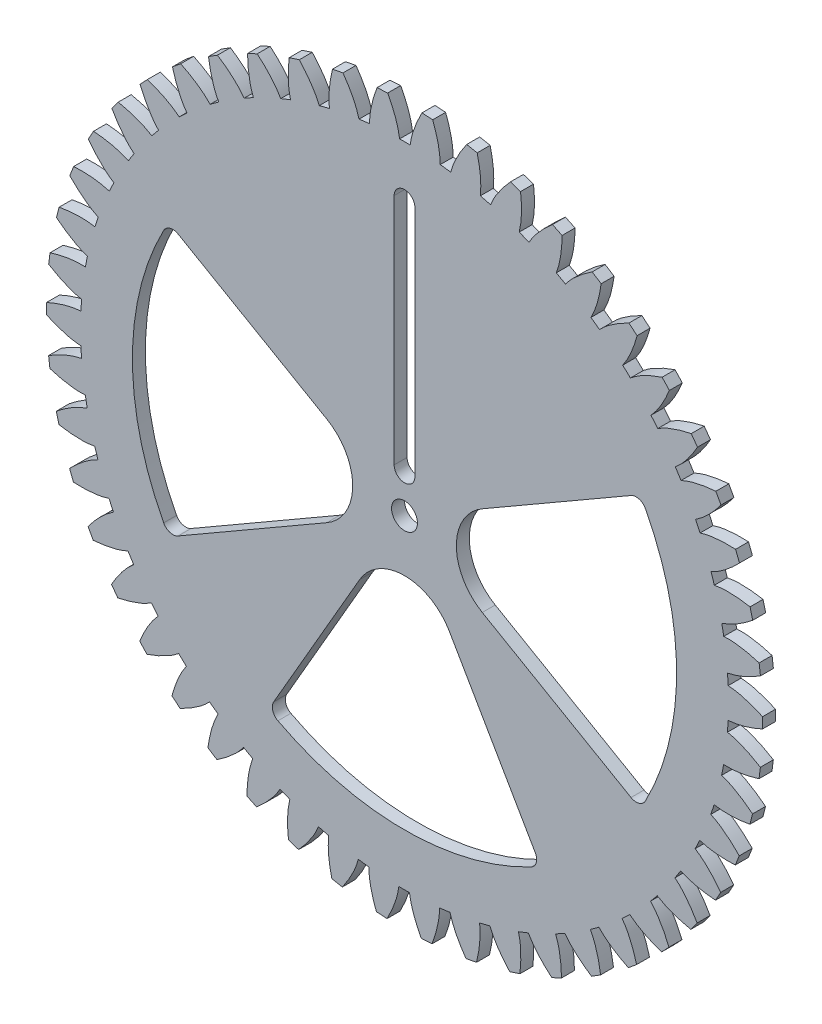
SolidWorks part; units mm, degrees
ref_plane "Front Plane" through (0, 0, 0) normal (0, 0, 1) x (1, 0, 0)
ref_plane "Top Plane" through (0, 0, 0) normal (0, 1, 0) x (1, 0, 0)
ref_plane "Right Plane" through (0, 0, 0) normal (1, 0, 0) x (0, 0, -1)
sketch "spiralSketch" plane through (0, 0, 0) normal (0, 0, 1) x (1, 0, 0)
  line L0 (30.4685, 172.8151) -> (35.6087, 171.8296)
  line L1 (8.5687, 175.2711) -> (13.7919, 174.9376)
  line L2 (51.8877, 167.6337) -> (56.8638, 166.0117)
  line L3 (72.4886, 159.8086) -> (77.2222, 157.5757)
  line L4 (91.9463, 149.4632) -> (96.3628, 146.6547)
  line L5 (109.954, 136.7607) -> (113.9836, 133.4208)
  line L6 (126.2277, 121.9014) -> (129.8069, 118.0828)
  line L7 (140.5106, 105.1197) -> (143.583, 100.8826)
  line L8 (152.5776, 86.6801) -> (155.0948, 82.0914)
  line L9 (162.2384, 66.8736) -> (164.1606, 62.0055)
  line L10 (169.3406, 46.0124) -> (170.6375, 40.9418)
  line L11 (173.7722, 24.4256) -> (174.4233, 19.2324)
  line L12 (175.4633, 2.4535) -> (175.4584, -2.7803)
  line L13 (174.3872, -19.5572) -> (173.7264, -24.7491)
  line L14 (170.5609, -41.2595) -> (169.2546, -46.3277)
  line L15 (164.0448, -62.3111) -> (162.1136, -67.1756)
  line L16 (154.9416, -82.38) -> (152.416, -86.9641)
  line L17 (143.3949, -101.1498) -> (140.3146, -105.3812)
  line L18 (129.5868, -118.3243) -> (126.0004, -122.1363)
  line L19 (113.735, -133.6328) -> (109.6992, -136.9652)
  line L20 (96.0895, -146.8339) -> (91.6679, -149.6342)
  line L21 (76.9287, -157.7193) -> (72.1909, -159.9433)
  line L22 (56.5546, -166.1173) -> (51.5754, -167.73)
  line L23 (35.2886, -171.8956) -> (30.1466, -172.8715)
  line L24 (13.4661, -174.963) -> (8.2423, -175.2868)
  line L25 (-8.5687, -175.2711) -> (-13.7919, -174.9376)
  line L26 (-30.4685, -172.8151) -> (-35.6087, -171.8296)
  line L27 (-51.8877, -167.6337) -> (-56.8638, -166.0117)
  line L28 (-72.4886, -159.8086) -> (-77.2222, -157.5757)
  line L29 (-91.9463, -149.4632) -> (-96.3628, -146.6547)
  line L30 (-109.954, -136.7607) -> (-113.9836, -133.4208)
  line L31 (-126.2277, -121.9014) -> (-129.8069, -118.0828)
  line L32 (-140.5106, -105.1197) -> (-143.583, -100.8826)
  line L33 (-152.5776, -86.6801) -> (-155.0948, -82.0914)
  line L34 (-162.2384, -66.8736) -> (-164.1606, -62.0055)
  line L35 (-169.3406, -46.0124) -> (-170.6375, -40.9418)
  line L36 (-173.7722, -24.4256) -> (-174.4233, -19.2324)
  line L37 (-175.4633, -2.4535) -> (-175.4584, 2.7803)
  line L38 (-174.3872, 19.5572) -> (-173.7264, 24.7491)
  line L39 (-170.5609, 41.2595) -> (-169.2546, 46.3277)
  line L40 (-164.0448, 62.3111) -> (-162.1136, 67.1756)
  line L41 (-154.9416, 82.38) -> (-152.416, 86.9641)
  line L42 (-143.3949, 101.1498) -> (-140.3146, 105.3812)
  line L43 (-129.5868, 118.3243) -> (-126.0004, 122.1363)
  line L44 (-113.735, 133.6328) -> (-109.6992, 136.9652)
  line L45 (-96.0895, 146.8339) -> (-91.6679, 149.6342)
  line L46 (-76.9287, 157.7193) -> (-72.1909, 159.9433)
  line L47 (-56.5546, 166.1173) -> (-51.5754, 167.73)
  line L48 (-35.2886, 171.8956) -> (-30.1466, 172.8715)
  line L49 (-13.4661, 174.963) -> (-8.2423, 175.2868)
  line L50 (0, 19.05) -> (0, 133.35) construction
  line L51 (-5.08, 19.05) -> (-5.08, 133.35)
  line L52 (5.08, 19.05) -> (5.08, 133.35)
  arc A2 (124.0747, 99.0305) -> (120.7741, 103.03) centre (0, 0) ccw
  arc A3 (135.5081, 82.6989) -> (132.7349, 87.0805) centre (0, 0) ccw
  arc A4 (144.8045, 65.0631) -> (142.6023, 69.7578) centre (0, 0) ccw
  arc A5 (151.8173, 46.4013) -> (150.2208, 51.3349) centre (0, 0) ccw
  arc A6 (156.4358, 27.0076) -> (155.4702, 32.1025) centre (0, 0) ccw
  arc A7 (158.5872, 7.1881) -> (158.2678, 12.3638) centre (0, 0) ccw
  arc A8 (155.3925, -32.4768) -> (156.3703, -27.3843) centre (0, 0) ccw
  arc A9 (158.2376, -12.7449) -> (158.5694, -7.5699) centre (0, 0) ccw
  arc A10 (150.0967, -51.6965) -> (151.7051, -46.7667) centre (0, 0) ccw
  arc A11 (142.4339, -70.101) -> (144.6474, -65.4117) centre (0, 0) ccw
  arc A12 (132.5248, -87.3999) -> (135.3086, -83.025) centre (0, 0) ccw
  arc A13 (120.5256, -103.3205) -> (123.8358, -99.329) centre (0, 0) ccw
  arc A14 (106.6258, -117.6117) -> (110.4101, -114.0665) centre (0, 0) ccw
  arc A15 (91.0443, -130.048) -> (95.2432, -127.0051) centre (0, 0) ccw
  arc A16 (74.0271, -140.4334) -> (78.5742, -137.9408) centre (0, 0) ccw
  arc A17 (55.8424, -148.6041) -> (60.6661, -146.701) centre (0, 0) ccw
  arc A18 (36.777, -154.4313) -> (41.8012, -153.1477) centre (0, 0) ccw
  arc A19 (17.1317, -157.8229) -> (22.2771, -157.1792) centre (0, 0) ccw
  arc A20 (-2.7839, -158.7256) -> (2.4016, -158.7318) centre (0, 0) ccw
  arc A21 (-22.6555, -157.1251) -> (-17.5117, -157.7812) centre (0, 0) ccw
  arc A22 (-42.1699, -153.0466) -> (-37.1488, -154.3422) centre (0, 0) ccw
  arc A23 (-61.0192, -146.5545) -> (-56.2001, -148.4692) centre (0, 0) ccw
  arc A24 (-78.9062, -137.7511) -> (-74.3651, -140.2548) centre (0, 0) ccw
  arc A25 (-95.5488, -126.7754) -> (-91.3573, -129.8284) centre (0, 0) ccw
  arc A26 (-110.6845, -113.8003) -> (-106.9087, -117.3546) centre (0, 0) ccw
  arc A27 (-124.0747, -99.0305) -> (-120.7741, -103.03) centre (0, 0) ccw
  arc A28 (-135.5081, -82.6989) -> (-132.7349, -87.0805) centre (0, 0) ccw
  arc A29 (-144.8045, -65.0631) -> (-142.6023, -69.7578) centre (0, 0) ccw
  arc A30 (-151.8173, -46.4013) -> (-150.2208, -51.3349) centre (0, 0) ccw
  arc A31 (-156.4358, -27.0076) -> (-155.4702, -32.1025) centre (0, 0) ccw
  arc A32 (-158.5872, -7.1881) -> (-158.2678, -12.3638) centre (0, 0) ccw
  arc A33 (-158.2376, 12.7449) -> (-158.5694, 7.5699) centre (0, 0) ccw
  arc A34 (-155.3925, 32.4768) -> (-156.3703, 27.3843) centre (0, 0) ccw
  arc A35 (-150.0967, 51.6965) -> (-151.7051, 46.7667) centre (0, 0) ccw
  arc A36 (-142.4339, 70.101) -> (-144.6474, 65.4117) centre (0, 0) ccw
  arc A37 (-132.5248, 87.3999) -> (-135.3086, 83.025) centre (0, 0) ccw
  arc A38 (-120.5256, 103.3205) -> (-123.8358, 99.329) centre (0, 0) ccw
  arc A39 (-106.6258, 117.6117) -> (-110.4101, 114.0665) centre (0, 0) ccw
  arc A40 (-91.0443, 130.048) -> (-95.2432, 127.0051) centre (0, 0) ccw
  arc A41 (-74.0271, 140.4334) -> (-78.5742, 137.9408) centre (0, 0) ccw
  arc A42 (-55.8424, 148.6041) -> (-60.6661, 146.701) centre (0, 0) ccw
  arc A43 (-36.777, 154.4313) -> (-41.8012, 153.1477) centre (0, 0) ccw
  arc A44 (-17.1317, 157.8229) -> (-22.2771, 157.1792) centre (0, 0) ccw
  arc A45 (2.7839, 158.7256) -> (-2.4016, 158.7318) centre (0, 0) ccw
  arc A46 (42.1699, 153.0466) -> (37.1488, 154.3422) centre (0, 0) ccw
  arc A47 (22.6555, 157.1251) -> (17.5117, 157.7812) centre (0, 0) ccw
  arc A48 (61.0192, 146.5545) -> (56.2001, 148.4692) centre (0, 0) ccw
  arc A49 (95.5488, 126.7754) -> (91.3573, 129.8284) centre (0, 0) ccw
  arc A50 (78.9062, 137.7511) -> (74.3651, 140.2548) centre (0, 0) ccw
  arc A51 (110.6845, 113.8003) -> (106.9087, 117.3546) centre (0, 0) ccw
  arc A52 (-5.08, 19.05) -> (5.08, 19.05) centre (0, 19.05) ccw
  arc A53 (5.08, 133.35) -> (-5.08, 133.35) centre (0, 133.35) ccw
  circle A54 centre (0, 0) radius 6.35
  spline S6 degree 3 poles (37.1488, 154.3422) (37.8319, 160.2093) (36.9788, 166.1292) (35.6087, 171.8296) knots 0 0 0 0 1 1 1 1
  spline S7 degree 3 poles (22.6555, 157.1251) (24.0894, 162.8561) (27.1178, 168.018) (30.4685, 172.8151) knots 0 0 0 0 1 1 1 1
  spline S8 degree 3 poles (2.7839, 158.7256) (3.4881, 164.5911) (5.8457, 170.0919) (8.5687, 175.2711) knots 0 0 0 0 1 1 1 1
  spline S9 degree 3 poles (17.5117, 157.7812) (17.4541, 163.6876) (15.8657, 169.4539) (13.7919, 174.9376) knots 0 0 0 0 1 1 1 1
  spline S10 degree 3 poles (56.2001, 148.4692) (57.6132, 154.2044) (57.5087, 160.1845) (56.8638, 166.0117) knots 0 0 0 0 1 1 1 1
  spline S11 degree 3 poles (42.1699, 153.0466) (44.3107, 158.5527) (47.9622, 163.2944) (51.8877, 167.6337) knots 0 0 0 0 1 1 1 1
  spline S12 degree 3 poles (74.3651, 140.2548) (76.4858, 145.7676) (77.1317, 151.7136) (77.2222, 157.5757) knots 0 0 0 0 1 1 1 1
  spline S13 degree 3 poles (61.0192, 146.5545) (63.8332, 151.7489) (68.0502, 155.9955) (72.4886, 159.8086) knots 0 0 0 0 1 1 1 1
  spline S14 degree 3 poles (91.3573, 129.8284) (94.1522, 135.032) (95.5383, 140.8502) (96.3628, 146.6547) knots 0 0 0 0 1 1 1 1
  spline S15 degree 3 poles (78.9062, 137.7511) (82.349, 142.5519) (87.065, 146.2365) (91.9463, 149.4632) knots 0 0 0 0 1 1 1 1
  spline S16 degree 3 poles (106.9087, 117.3546) (110.3338, 122.1668) (112.4381, 127.7654) (113.9836, 133.4208) knots 0 0 0 0 1 1 1 1
  spline S17 degree 3 poles (95.5488, 126.7754) (99.5662, 131.1067) (104.7068, 134.1712) (109.954, 136.7607) knots 0 0 0 0 1 1 1 1
  spline S18 degree 3 poles (120.7741, 103.03) (124.7753, 107.375) (127.5648, 112.6657) (129.8069, 118.0828) knots 0 0 0 0 1 1 1 1
  spline S19 degree 3 poles (110.6845, 113.8003) (115.2131, 117.594) (120.6972, 119.99) (126.2277, 121.9014) knots 0 0 0 0 1 1 1 1
  spline S20 degree 3 poles (132.7349, 87.0805) (137.2491, 90.8898) (140.6796, 95.7892) (143.583, 100.8826) knots 0 0 0 0 1 1 1 1
  spline S21 degree 3 poles (124.0747, 99.0305) (129.0431, 102.2267) (134.7842, 103.9165) (140.5106, 105.1197) knots 0 0 0 0 1 1 1 1
  spline S22 degree 3 poles (142.6023, 69.7578) (147.5584, 72.9712) (151.5759, 77.402) (155.0948, 82.0914) knots 0 0 0 0 1 1 1 1
  spline S23 degree 3 poles (135.5081, 82.6989) (140.8379, 85.2472) (146.7456, 86.2041) (152.5776, 86.6801) knots 0 0 0 0 1 1 1 1
  spline S24 degree 3 poles (150.2208, 51.3349) (155.5406, 53.9019) (160.0817, 57.7942) (164.1606, 62.0055) knots 0 0 0 0 1 1 1 1
  spline S25 degree 3 poles (144.8045, 65.0631) (150.4117, 66.9233) (156.3927, 67.1322) (162.2384, 66.8736) knots 0 0 0 0 1 1 1 1
  spline S26 degree 3 poles (155.4702, 32.1025) (161.0698, 33.9824) (166.063, 37.2749) (170.6375, 40.9418) knots 0 0 0 0 1 1 1 1
  spline S27 degree 3 poles (151.8173, 46.4013) (157.6133, 47.544) (163.5734, 47.0017) (169.3406, 46.0124) knots 0 0 0 0 1 1 1 1
  spline S28 degree 3 poles (158.2678, 12.3638) (164.0588, 13.5271) (169.4253, 16.1678) (174.4233, 19.2324) knots 0 0 0 0 1 1 1 1
  spline S29 degree 3 poles (156.4358, 27.0076) (162.3294, 27.415) (168.1745, 26.1299) (173.7722, 24.4256) knots 0 0 0 0 1 1 1 1
  spline S30 degree 3 poles (158.5694, -7.5699) (164.4606, -7.1416) (170.1157, -5.1943) (175.4584, -2.7803) knots 0 0 0 0 1 1 1 1
  spline S31 degree 3 poles (158.5872, 7.1881) (164.4854, 6.8535) (170.1233, 4.846) (175.4633, 2.4535) knots 0 0 0 0 1 1 1 1
  spline S32 degree 3 poles (156.3703, -27.3843) (162.2687, -27.6977) (168.1233, -26.4745) (173.7264, -24.7491) knots 0 0 0 0 1 1 1 1
  spline S33 degree 3 poles (158.2376, -12.7449) (164.0473, -13.816) (169.3892, -16.5143) (174.3872, -19.5572) knots 0 0 0 0 1 1 1 1
  spline S34 degree 3 poles (151.7051, -46.7667) (157.5177, -47.8169) (163.4794, -47.3372) (169.2546, -46.3277) knots 0 0 0 0 1 1 1 1
  spline S35 degree 3 poles (155.3925, -32.4768) (161.0221, -34.2676) (165.9837, -37.6142) (170.5609, -41.2595) knots 0 0 0 0 1 1 1 1
  spline S36 degree 3 poles (144.6474, -65.4117) (150.2826, -67.1821) (156.2574, -67.4533) (162.1136, -67.1756) knots 0 0 0 0 1 1 1 1
  spline S37 degree 3 poles (150.0967, -51.6965) (155.4576, -54.1789) (159.9606, -58.1209) (164.0448, -62.3111) knots 0 0 0 0 1 1 1 1
  spline S38 degree 3 poles (135.3086, -83.025) (140.6774, -85.4877) (146.5711, -86.5057) (152.416, -86.9641) knots 0 0 0 0 1 1 1 1
  spline S39 degree 3 poles (142.4339, -70.101) (147.4413, -73.2356) (151.4148, -77.7109) (154.9416, -82.38) knots 0 0 0 0 1 1 1 1
  spline S40 degree 3 poles (123.8358, -99.329) (128.8537, -102.4452) (134.5733, -104.1938) (140.3146, -105.3812) knots 0 0 0 0 1 1 1 1
  spline S41 degree 3 poles (132.5248, -87.3999) (137.0998, -91.1375) (140.481, -96.0755) (143.3949, -101.1498) knots 0 0 0 0 1 1 1 1
  spline S42 degree 3 poles (110.4101, -114.0665) (114.9978, -117.787) (120.4532, -120.2387) (126.0004, -122.1363) knots 0 0 0 0 1 1 1 1
  spline S43 degree 3 poles (120.5256, -103.3205) (124.5962, -107.602) (127.3319, -112.9248) (129.5868, -118.3243) knots 0 0 0 0 1 1 1 1
  spline S44 degree 3 poles (95.2432, -127.0051) (99.3284, -131.2713) (104.4335, -134.3874) (109.6992, -136.9652) knots 0 0 0 0 1 1 1 1
  spline S45 degree 3 poles (106.6258, -117.6117) (110.1276, -122.3696) (112.1746, -127.9933) (113.735, -133.6328) knots 0 0 0 0 1 1 1 1
  spline S46 degree 3 poles (78.5742, -137.9408) (82.0925, -142.6853) (86.7668, -146.4167) (91.6679, -149.6342) knots 0 0 0 0 1 1 1 1
  spline S47 degree 3 poles (91.0443, -130.048) (93.9223, -135.2073) (95.2482, -141.0432) (96.0895, -146.8339) knots 0 0 0 0 1 1 1 1
  spline S48 degree 3 poles (60.6661, -146.701) (63.562, -151.8491) (67.7318, -156.1369) (72.1909, -159.9433) knots 0 0 0 0 1 1 1 1
  spline S49 degree 3 poles (74.0271, -140.4334) (76.2357, -145.9127) (76.8198, -151.8688) (76.9287, -157.7193) knots 0 0 0 0 1 1 1 1
  spline S50 degree 3 poles (41.8012, -153.1477) (44.029, -158.6182) (47.6286, -163.3948) (51.5754, -167.73) knots 0 0 0 0 1 1 1 1
  spline S51 degree 3 poles (55.8424, -148.6041) (57.3469, -154.317) (57.1798, -160.2994) (56.5546, -166.1173) knots 0 0 0 0 1 1 1 1
  spline S52 degree 3 poles (22.2771, -157.1792) (23.8017, -162.8857) (26.7742, -168.0758) (30.1466, -172.8715) knots 0 0 0 0 1 1 1 1
  spline S53 degree 3 poles (36.777, -154.4313) (37.5536, -160.2877) (36.6381, -166.2019) (35.2886, -171.8956) knots 0 0 0 0 1 1 1 1
  spline S54 degree 3 poles (2.4016, -158.7318) (3.1991, -164.5844) (5.4976, -170.1062) (8.2423, -175.2868) knots 0 0 0 0 1 1 1 1
  spline S55 degree 3 poles (17.1317, -157.8229) (17.1681, -163.7304) (15.5186, -169.4833) (13.4661, -174.963) knots 0 0 0 0 1 1 1 1
  spline S56 degree 3 poles (-17.5117, -157.7812) (-17.4541, -163.6876) (-15.8657, -169.4539) (-13.7919, -174.9376) knots 0 0 0 0 1 1 1 1
  spline S57 degree 3 poles (-2.7839, -158.7256) (-3.4881, -164.5911) (-5.8457, -170.0919) (-8.5687, -175.2711) knots 0 0 0 0 1 1 1 1
  spline S58 degree 3 poles (-37.1488, -154.3422) (-37.8319, -160.2093) (-36.9788, -166.1292) (-35.6087, -171.8296) knots 0 0 0 0 1 1 1 1
  spline S59 degree 3 poles (-22.6555, -157.1251) (-24.0894, -162.8561) (-27.1178, -168.018) (-30.4685, -172.8151) knots 0 0 0 0 1 1 1 1
  spline S60 degree 3 poles (-56.2001, -148.4692) (-57.6132, -154.2044) (-57.5087, -160.1845) (-56.8638, -166.0117) knots 0 0 0 0 1 1 1 1
  spline S61 degree 3 poles (-42.1699, -153.0466) (-44.3107, -158.5527) (-47.9622, -163.2944) (-51.8877, -167.6337) knots 0 0 0 0 1 1 1 1
  spline S62 degree 3 poles (-74.3651, -140.2548) (-76.4858, -145.7676) (-77.1317, -151.7136) (-77.2222, -157.5757) knots 0 0 0 0 1 1 1 1
  spline S63 degree 3 poles (-61.0192, -146.5545) (-63.8332, -151.7489) (-68.0502, -155.9955) (-72.4886, -159.8086) knots 0 0 0 0 1 1 1 1
  spline S64 degree 3 poles (-91.3573, -129.8284) (-94.1522, -135.032) (-95.5383, -140.8502) (-96.3628, -146.6547) knots 0 0 0 0 1 1 1 1
  spline S65 degree 3 poles (-78.9062, -137.7511) (-82.349, -142.5519) (-87.065, -146.2365) (-91.9463, -149.4632) knots 0 0 0 0 1 1 1 1
  spline S66 degree 3 poles (-106.9087, -117.3546) (-110.3338, -122.1668) (-112.4381, -127.7654) (-113.9836, -133.4208) knots 0 0 0 0 1 1 1 1
  spline S67 degree 3 poles (-95.5488, -126.7754) (-99.5662, -131.1067) (-104.7068, -134.1712) (-109.954, -136.7607) knots 0 0 0 0 1 1 1 1
  spline S68 degree 3 poles (-120.7741, -103.03) (-124.7753, -107.375) (-127.5648, -112.6657) (-129.8069, -118.0828) knots 0 0 0 0 1 1 1 1
  spline S69 degree 3 poles (-110.6845, -113.8003) (-115.2131, -117.594) (-120.6972, -119.99) (-126.2277, -121.9014) knots 0 0 0 0 1 1 1 1
  spline S70 degree 3 poles (-132.7349, -87.0805) (-137.2491, -90.8898) (-140.6796, -95.7892) (-143.583, -100.8826) knots 0 0 0 0 1 1 1 1
  spline S71 degree 3 poles (-124.0747, -99.0305) (-129.0431, -102.2267) (-134.7842, -103.9165) (-140.5106, -105.1197) knots 0 0 0 0 1 1 1 1
  spline S72 degree 3 poles (-142.6023, -69.7578) (-147.5584, -72.9712) (-151.5759, -77.402) (-155.0948, -82.0914) knots 0 0 0 0 1 1 1 1
  spline S73 degree 3 poles (-135.5081, -82.6989) (-140.8379, -85.2472) (-146.7456, -86.2041) (-152.5776, -86.6801) knots 0 0 0 0 1 1 1 1
  spline S74 degree 3 poles (-150.2208, -51.3349) (-155.5406, -53.9019) (-160.0817, -57.7942) (-164.1606, -62.0055) knots 0 0 0 0 1 1 1 1
  spline S75 degree 3 poles (-144.8045, -65.0631) (-150.4117, -66.9233) (-156.3927, -67.1322) (-162.2384, -66.8736) knots 0 0 0 0 1 1 1 1
  spline S76 degree 3 poles (-155.4702, -32.1025) (-161.0698, -33.9824) (-166.063, -37.2749) (-170.6375, -40.9418) knots 0 0 0 0 1 1 1 1
  spline S77 degree 3 poles (-151.8173, -46.4013) (-157.6133, -47.544) (-163.5734, -47.0017) (-169.3406, -46.0124) knots 0 0 0 0 1 1 1 1
  spline S78 degree 3 poles (-158.2678, -12.3638) (-164.0588, -13.5271) (-169.4253, -16.1678) (-174.4233, -19.2324) knots 0 0 0 0 1 1 1 1
  spline S79 degree 3 poles (-156.4358, -27.0076) (-162.3294, -27.415) (-168.1745, -26.1299) (-173.7722, -24.4256) knots 0 0 0 0 1 1 1 1
  spline S80 degree 3 poles (-158.5694, 7.5699) (-164.4606, 7.1416) (-170.1157, 5.1943) (-175.4584, 2.7803) knots 0 0 0 0 1 1 1 1
  spline S81 degree 3 poles (-158.5872, -7.1881) (-164.4854, -6.8535) (-170.1233, -4.846) (-175.4633, -2.4535) knots 0 0 0 0 1 1 1 1
  spline S82 degree 3 poles (-156.3703, 27.3843) (-162.2687, 27.6977) (-168.1233, 26.4745) (-173.7264, 24.7491) knots 0 0 0 0 1 1 1 1
  spline S83 degree 3 poles (-158.2376, 12.7449) (-164.0473, 13.816) (-169.3892, 16.5143) (-174.3872, 19.5572) knots 0 0 0 0 1 1 1 1
  spline S84 degree 3 poles (-151.7051, 46.7667) (-157.5177, 47.8169) (-163.4794, 47.3372) (-169.2546, 46.3277) knots 0 0 0 0 1 1 1 1
  spline S85 degree 3 poles (-155.3925, 32.4768) (-161.0221, 34.2676) (-165.9837, 37.6142) (-170.5609, 41.2595) knots 0 0 0 0 1 1 1 1
  spline S86 degree 3 poles (-144.6474, 65.4117) (-150.2826, 67.1821) (-156.2574, 67.4533) (-162.1136, 67.1756) knots 0 0 0 0 1 1 1 1
  spline S87 degree 3 poles (-150.0967, 51.6965) (-155.4576, 54.1789) (-159.9606, 58.1209) (-164.0448, 62.3111) knots 0 0 0 0 1 1 1 1
  spline S88 degree 3 poles (-135.3086, 83.025) (-140.6774, 85.4877) (-146.5711, 86.5057) (-152.416, 86.9641) knots 0 0 0 0 1 1 1 1
  spline S89 degree 3 poles (-142.4339, 70.101) (-147.4413, 73.2356) (-151.4148, 77.7109) (-154.9416, 82.38) knots 0 0 0 0 1 1 1 1
  spline S90 degree 3 poles (-123.8358, 99.329) (-128.8537, 102.4452) (-134.5733, 104.1938) (-140.3146, 105.3812) knots 0 0 0 0 1 1 1 1
  spline S91 degree 3 poles (-132.5248, 87.3999) (-137.0998, 91.1375) (-140.481, 96.0755) (-143.3949, 101.1498) knots 0 0 0 0 1 1 1 1
  spline S92 degree 3 poles (-110.4101, 114.0665) (-114.9978, 117.787) (-120.4532, 120.2387) (-126.0004, 122.1363) knots 0 0 0 0 1 1 1 1
  spline S93 degree 3 poles (-120.5256, 103.3205) (-124.5962, 107.602) (-127.3319, 112.9248) (-129.5868, 118.3243) knots 0 0 0 0 1 1 1 1
  spline S94 degree 3 poles (-95.2432, 127.0051) (-99.3284, 131.2713) (-104.4335, 134.3874) (-109.6992, 136.9652) knots 0 0 0 0 1 1 1 1
  spline S95 degree 3 poles (-106.6258, 117.6117) (-110.1276, 122.3696) (-112.1746, 127.9933) (-113.735, 133.6328) knots 0 0 0 0 1 1 1 1
  spline S96 degree 3 poles (-78.5742, 137.9408) (-82.0925, 142.6853) (-86.7668, 146.4167) (-91.6679, 149.6342) knots 0 0 0 0 1 1 1 1
  spline S97 degree 3 poles (-91.0443, 130.048) (-93.9223, 135.2073) (-95.2482, 141.0432) (-96.0895, 146.8339) knots 0 0 0 0 1 1 1 1
  spline S98 degree 3 poles (-60.6661, 146.701) (-63.562, 151.8491) (-67.7318, 156.1369) (-72.1909, 159.9433) knots 0 0 0 0 1 1 1 1
  spline S99 degree 3 poles (-74.0271, 140.4334) (-76.2357, 145.9127) (-76.8198, 151.8688) (-76.9287, 157.7193) knots 0 0 0 0 1 1 1 1
  spline S100 degree 3 poles (-41.8012, 153.1477) (-44.029, 158.6182) (-47.6286, 163.3948) (-51.5754, 167.73) knots 0 0 0 0 1 1 1 1
  spline S101 degree 3 poles (-55.8424, 148.6041) (-57.3469, 154.317) (-57.1798, 160.2994) (-56.5546, 166.1173) knots 0 0 0 0 1 1 1 1
  spline S102 degree 3 poles (-22.2771, 157.1792) (-23.8017, 162.8857) (-26.7742, 168.0758) (-30.1466, 172.8715) knots 0 0 0 0 1 1 1 1
  spline S103 degree 3 poles (-36.777, 154.4313) (-37.5536, 160.2877) (-36.6381, 166.2019) (-35.2886, 171.8956) knots 0 0 0 0 1 1 1 1
  spline S104 degree 3 poles (-2.4016, 158.7318) (-3.1991, 164.5844) (-5.4976, 170.1062) (-8.2423, 175.2868) knots 0 0 0 0 1 1 1 1
  spline S105 degree 3 poles (-17.1317, 157.8229) (-17.1681, 163.7304) (-15.5186, 169.4833) (-13.4661, 174.963) knots 0 0 0 0 1 1 1 1
  point P3 (0, 76.2)
  point P211 (0, 0)
  dimension "D3" = 317.5
  dimension "D5" = 5.08
  dimension "D6" = 12.7
  dimension "D1" = 19.05
  dimension "D2" = 133.35
  dimension "D4" = 50
extrude "Boss-Extrude1" add sketch "spiralSketch" along normal blind 6.35
sketch "Sketch1" plane through (0, 0, 6.35) normal (0, 0, 1) x (1, 0, 0)
  line L0 (38.1, 21.997) -> (110.9979, 64.0847)
  line L1 (110.9979, -64.0847) -> (38.1, -21.997)
  line L2 (0, 19.05) -> (0, 133.35) construction
  line L3 (-64.0847, -110.9979) -> (-21.997, -38.1)
  line L4 (21.997, -38.1) -> (64.0847, -110.9979)
  line L5 (-110.9979, 64.0847) -> (-38.1, 21.997)
  line L6 (-38.1, -21.997) -> (-110.9979, -64.0847)
  line L7 (0, 0) -> (38.1, -21.997) construction
  line L8 (0, 0) -> (-21.997, -38.1) construction
  arc A0 (110.9979, 64.0847) -> (118.0345, 62.049) centre (113.5379, 59.6853) cw
  arc A5 (118.0345, 62.049) -> (118.0345, -62.049) centre (0, 0) cw
  arc A6 (118.0345, -62.049) -> (110.9979, -64.0847) centre (113.5379, -59.6853) cw
  arc A7 (38.1, -21.997) -> (38.1, 21.997) centre (50.8, 0) cw
  arc A8 (-21.997, -38.1) -> (21.997, -38.1) centre (0, -50.8) cw
  arc A9 (64.0847, -110.9979) -> (62.049, -118.0345) centre (59.6853, -113.5379) cw
  arc A10 (62.049, -118.0345) -> (-62.049, -118.0345) centre (0, 0) cw
  arc A11 (-62.049, -118.0345) -> (-64.0847, -110.9979) centre (-59.6853, -113.5379) cw
  arc A12 (-38.1, 21.997) -> (-38.1, -21.997) centre (-50.8, 0) cw
  arc A13 (-110.9979, -64.0847) -> (-118.0345, -62.049) centre (-113.5379, -59.6853) cw
  arc A14 (-118.0345, -62.049) -> (-118.0345, 62.049) centre (0, 0) cw
  arc A15 (-118.0345, 62.049) -> (-110.9979, 64.0847) centre (-113.5379, 59.6853) cw
  dimension "D2" = 5.08
  dimension "D3" = 133.35
  dimension "D1" = 60
  dimension "D4" = 60
  dimension "D5" = 50.8
  dimension "D7" = 90
  dimension "D6" = 3
extrude "Cut-Extrude1" cut sketch "Sketch1" against normal up to surface (6.35 mm away) up to face at (0, 0, 0)
equation "\"D1@spiralSketch\"=\"slotStart@405TermProject.Assembly\""
equation "\"D2@spiralSketch\"=\"slotEnd@405TermProject.Assembly\""
equation "\"D5@spiralSketch\"=\"slotRadius@405TermProject.Assembly\""
equation "\"D1@Boss-Extrude1\"=\"diskThickness@405TermProject.Assembly\""
equation "\"D1@Sketch1\"=\"reliefAngle@405TermProject.Assembly\""
equation "\"D2@Sketch1\"=\"reliefRoundRad@405TermProject.Assembly\""
equation "\"D3@Sketch1\"=\"releifRadOuter@405TermProject.Assembly\""
equation "\"D4@Sketch1\"=\"reliefFromSlotAngle@405TermProject.Assembly\""
equation "\"D5@Sketch1\"=\"reliefRadInner@405TermProject.Assembly\""
equation "\"D6@Sketch1\"=\"reliefNumber@405TermProject.Assembly\""
equation "\"D7@Sketch1\"=.5*\"reliefAngle@405TermProject.Assembly\"+\"reliefAngle@405TermProject.Assembly\""
